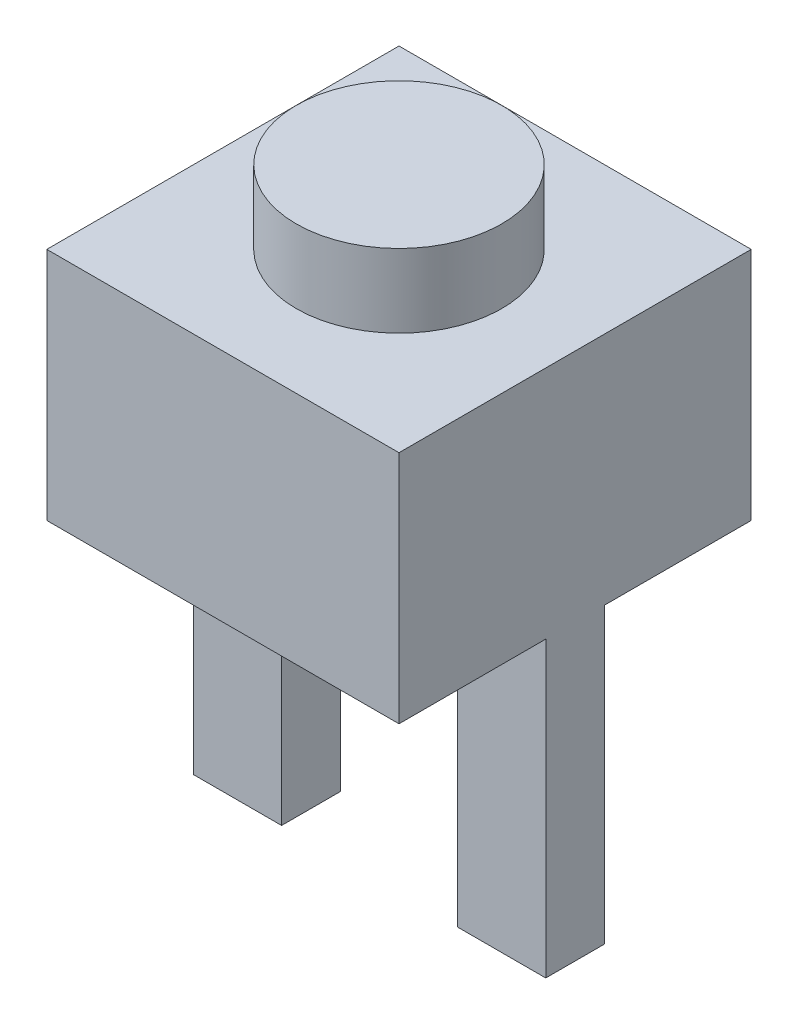
SolidWorks part; units mm, degrees
ref_plane "Front Plane" through (0, 0, 0) normal (0, 0, 1) x (1, 0, 0)
ref_plane "Top Plane" through (0, 0, 0) normal (0, 1, 0) x (1, 0, 0)
ref_plane "Right Plane" through (0, 0, 0) normal (1, 0, 0) x (0, 0, -1)
sketch "Sketch1" plane through (0, 0, 0) normal (0, 1, 0) x (1, 0, 0)
  line L1 (-3, -3) -> (3, -3)
  line L2 (-3, -3) -> (-3, 3)
  line L3 (-3, 3) -> (3, 3)
  line L4 (3, -3) -> (3, 3)
  line L5 (-3, -3) -> (3, 3) construction
  line L6 (-3, 3) -> (3, -3) construction
  point P0 (0, 0)
  dimension "D1" = 6
  dimension "D2" = 6
extrude "Boss-Extrude1" add sketch "Sketch1" along normal blind 4 contours L3 L4 L1 L2
sketch "Sketch2" plane through (0, 4, 0) normal (0, 1, 0) x (1, 0, 0)
  circle A0 centre (0, 0) radius 1.75
  dimension "D1" = 3.5
extrude "Boss-Extrude2" add sketch "Sketch2" along normal blind 1.25
sketch "Sketch3" plane through (0, 0, 0) normal (0, -1, 0) x (1, 0, 0)
  line L0 (3, 3) -> (3, -3) construction
  line L1 (-3, -0.5) -> (3, -0.5) construction
  line L2 (-3, -0.5) -> (-3, 0.5) construction
  line L3 (-3, 0.5) -> (3, 0.5) construction
  line L4 (3, -0.5) -> (3, 0.5) construction
  line L5 (-3, -0.5) -> (3, 0.5) construction
  line L6 (-3, 0.5) -> (3, -0.5) construction
  line L8 (3, 0.5) -> (1.5, 0.5)
  line L9 (3, 0.5) -> (3, -0.5)
  line L10 (3, -0.5) -> (1.5, -0.5)
  line L11 (1.5, 0.5) -> (1.5, -0.5)
  line L12 (-3, 0.5) -> (-1.5, 0.5)
  line L13 (-3, 0.5) -> (-3, -0.5)
  line L14 (-3, -0.5) -> (-1.5, -0.5)
  line L15 (-1.5, 0.5) -> (-1.5, -0.5)
  point P0 (0, 0)
  point P12 (0, 0)
  line M3 (3, -3) -> (3, 3)
  dimension "D1" = 1
  dimension "D2" = 1.5
  dimension "D3" = 1.5
extrude "Boss-Extrude3" add sketch "Sketch3" along normal blind 5 contours L8 L11 L10 M3 | L12 L15 L14 L13
